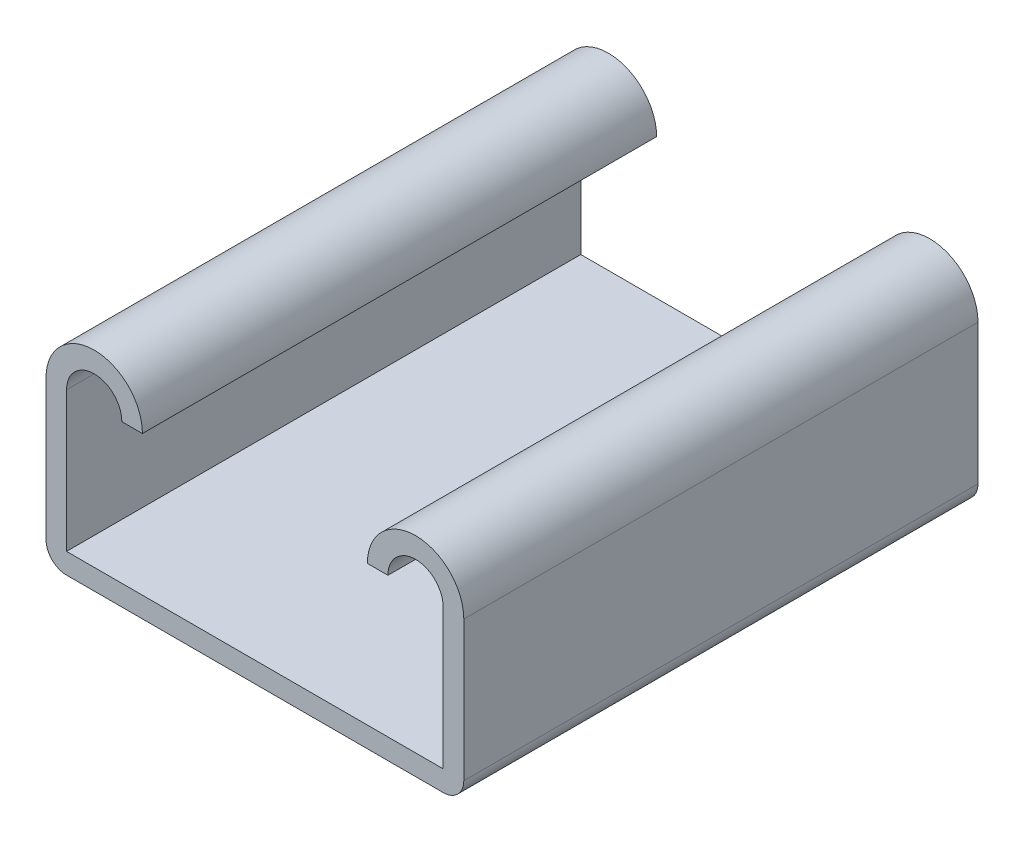
SolidWorks part; units mm, degrees
ref_plane "Plane1" through (0, 0, 0) normal (0, 0, 1) x (1, 0, 0)
ref_plane "Plane2" through (0, 0, 0) normal (0, 1, 0) x (1, 0, 0)
ref_plane "Plane3" through (0, 0, 0) normal (1, 0, 0) x (0, 0, -1)
sketch "Sketch1" plane through (0, 0, 0) normal (0, 0, 1) x (1, 0, 0)
  line L0 (-10.3188, 3.7909) -> (-10.3188, -3.1242)
  line L1 (-9.3027, -4.1402) -> (9.3028, -4.1402)
  line L2 (10.3188, -3.1242) -> (10.3188, 3.7909)
  line L3 (-6.5723, 3.7909) -> (-5.5563, 3.7909)
  line L4 (5.5562, 3.7909) -> (6.5722, 3.7909)
  line L6 (-9.3028, 3.7909) -> (-9.3027, -3.1242)
  line L7 (-9.3027, -3.1242) -> (9.3027, -3.1242)
  line L8 (9.3027, -3.1242) -> (9.3027, 3.7909)
  line L10 (-25.4, 6.1722) -> (25.4, 6.1722) construction
  arc A0 (10.3188, 3.7909) -> (5.5562, 3.7909) centre (7.9375, 3.7909) ccw
  arc A1 (-10.3188, 3.7909) -> (-5.5563, 3.7909) centre (-7.9375, 3.7909) cw
  arc A2 (-9.3027, -4.1402) -> (-10.3188, -3.1242) centre (-9.3027, -3.1242) cw
  arc A3 (9.3028, -4.1402) -> (10.3188, -3.1242) centre (9.3028, -3.1242) ccw
  arc A4 (-9.3028, 3.7909) -> (-6.5723, 3.7909) centre (-7.9375, 3.7909) cw
  arc A5 (9.3027, 3.7909) -> (6.5722, 3.7909) centre (7.9375, 3.7909) ccw
  dimension "D1" = 1.016
  dimension "D3" = 10.3187
  dimension "Width" = 20.6375
  dimension "D5" = 4.1402
  dimension "D8" = 6.1722
  dimension "D2" = 4.7625
  dimension "D4" = 1.016
  dimension "D6" = 11.1125
  dimension "D7" = 4.7625
  dimension "gauge" = 1.016
extrude "Base-Extrude" add sketch "Sketch1" along normal mid plane 25.4
equation "\"D3@Sketch1\" = \"Width@Sketch1\" / 2"
equation "\"D1@Sketch1\" = \"gauge@Sketch1\""
